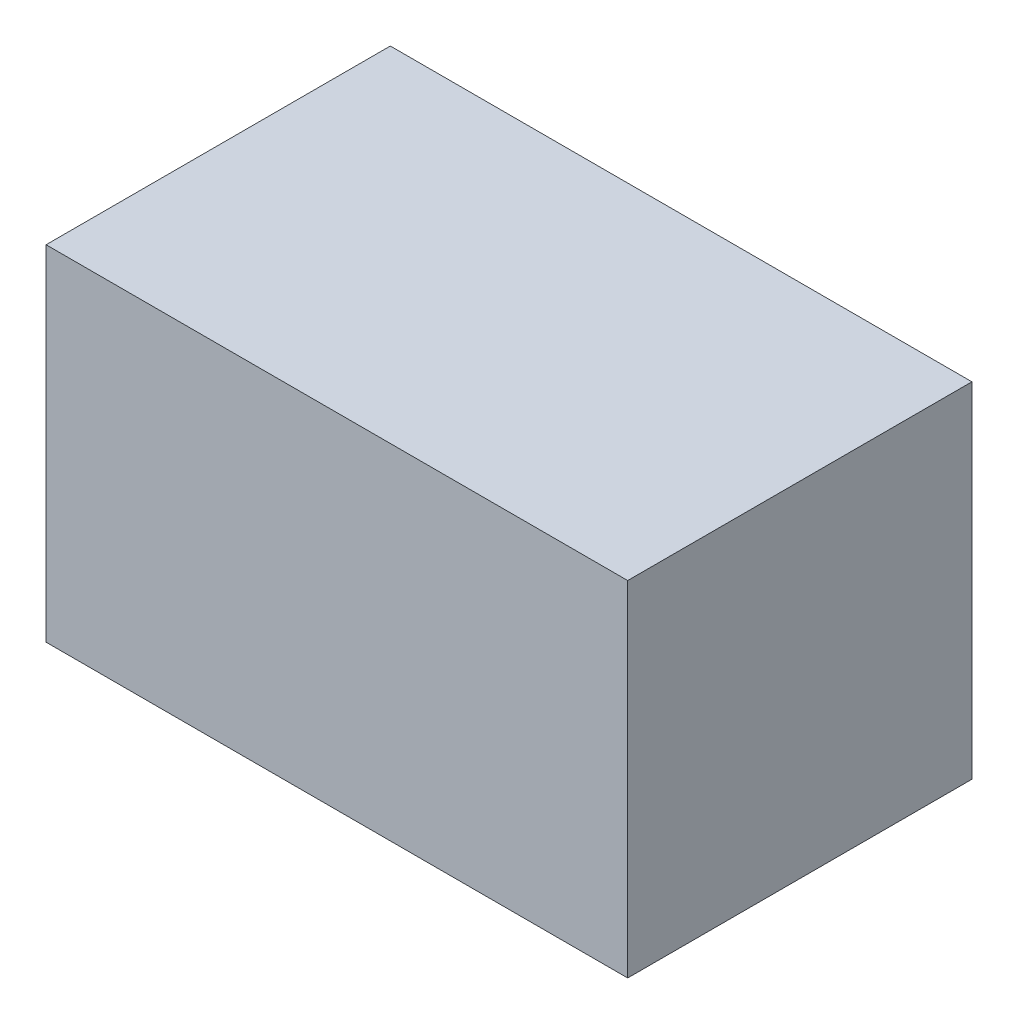
SolidWorks part; units mm, degrees
material "Eau"
ref_plane "Plan de face" through (0, 0, 0) normal (0, 0, 1) x (1, 0, 0)
ref_plane "Plan de dessus" through (0, 0, 0) normal (0, 1, 0) x (1, 0, 0)
ref_plane "Plan de droite" through (0, 0, 0) normal (1, 0, 0) x (0, 0, -1)
sketch "Esquisse1" plane through (0, 0, 0) normal (0, 0, 1) x (1, 0, 0)
  line L1 (245, -145) -> (-245, -145)
  line L2 (245, -145) -> (245, 145)
  line L3 (245, 145) -> (-245, 145)
  line L4 (-245, -145) -> (-245, 145)
  line L5 (245, -145) -> (-245, 145) construction
  line L6 (245, 145) -> (-245, -145) construction
  point P0 (0, 0)
  dimension "D1" = 290
  dimension "D2" = 490
extrude "Boss.-Extru.1" add sketch "Esquisse1" along normal blind 290
